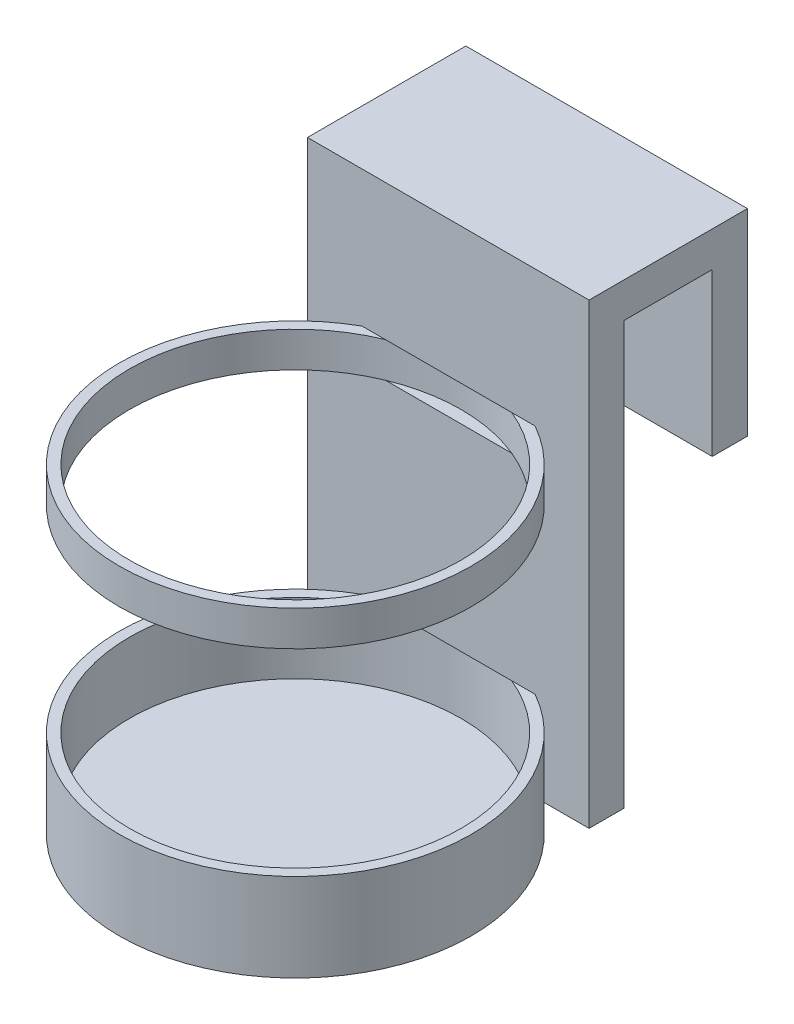
SolidWorks part; units mm, degrees
ref_plane "Front Plane" through (0, 0, 0) normal (0, 0, 1) x (1, 0, 0)
ref_plane "Top Plane" through (0, 0, 0) normal (0, 1, 0) x (1, 0, 0)
ref_plane "Right Plane" through (0, 0, 0) normal (1, 0, 0) x (0, 0, -1)
sketch "Sketch1" plane through (0, 0, 0) normal (1, 0, 0) x (0, 0, -1)
  line L0 (40.6098, 22.6585) -> (40.6098, 78.6585)
  line L1 (40.6098, 78.6585) -> (-4.3902, 78.6585)
  line L2 (-4.3902, 78.6585) -> (-4.3902, -51.3415)
  line L3 (-4.3902, -51.3415) -> (5.6098, -51.3415)
  line L4 (5.6098, -51.3415) -> (5.6098, 68.6585)
  line L5 (5.6098, 68.6585) -> (30.6098, 68.6585)
  line L6 (30.6098, 68.6585) -> (30.6098, 22.6585)
  line L7 (30.6098, 22.6585) -> (40.6098, 22.6585)
  dimension "D1" = 10
  dimension "D2" = 10
  dimension "D3" = 25
  dimension "D4" = 120
  dimension "D5" = 46
  dimension "D6" = 10
extrude "Boss-Extrude1" add sketch "Sketch1" along normal blind 80
sketch3d "3DSketch1" plane through (0, 0, 0) normal (0, 0, 1) x (1, 0, 0)
  dimension "D1" = 30
sketch "Sketch2" plane through (0, 30, 0) normal (0, 1, 0) x (1, 0, 0)
  circle A0 centre (40.0882, -47.9325) radius 50
extrude "Boss-Extrude2" add sketch "Sketch2" along normal blind 10
sketch "Sketch3" plane through (0, 40, 0) normal (0, 1, 0) x (1, 0, 0)
  circle A0 centre (40.0882, -47.9325) radius 47.0933
extrude "Cut-Extrude1" cut sketch "Sketch3" against normal blind 10
sketch3d "3DSketch2" plane through (0, 0, 0) normal (0, 0, 1) x (1, 0, 0)
  dimension "D1" = 51
sketch "Sketch4" plane through (0, -51, 0) normal (0, 1, 0) x (1, 0, 0)
  circle A0 centre (40.0882, -47.9325) radius 50
extrude "Boss-Extrude3" add sketch "Sketch4" along normal blind 25
sketch "Sketch5" plane through (0, -26, 0) normal (0, 1, 0) x (1, 0, 0)
  circle A0 centre (40.0882, -47.9325) radius 47.0933
extrude "Cut-Extrude2" cut sketch "Sketch5" against normal blind 20
